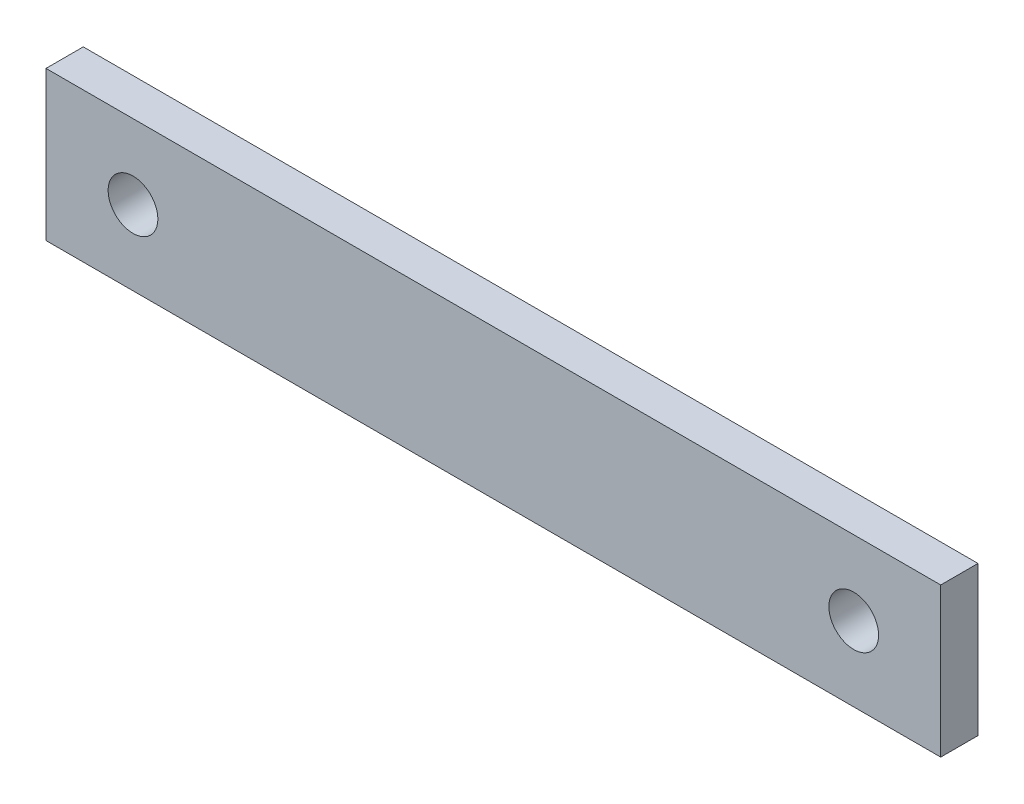
SolidWorks part; units mm, degrees
ref_plane "Plan de face" through (0, 0, 0) normal (0, 0, 1) x (1, 0, 0)
ref_plane "Plan de dessus" through (0, 0, 0) normal (0, 1, 0) x (1, 0, 0)
ref_plane "Plan de droite" through (0, 0, 0) normal (1, 0, 0) x (0, 0, -1)
sketch "Esquisse1" plane through (0, 0, 0) normal (0, 0, 1) x (1, 0, 0)
  line L0 (-24.595, 4.4308) -> (18.605, 4.4308)
  line L1 (-24.595, 4.4308) -> (-24.595, -2.7692)
  line L2 (-24.595, -2.7692) -> (18.605, -2.7692)
  line L3 (18.605, -2.7692) -> (18.605, 4.4308)
  dimension "D1" = 43.2
  dimension "D2" = 7.2
extrude "Boss.-Extru.1" add sketch "Esquisse1" along normal blind 1.8
sketch "Esquisse2" plane through (0, 0, 0) normal (0, 0, 1) x (1, 0, 0)
  line L0 (-24.595, 0.8308) -> (18.605, 0.8308) construction
  line L1 (-24.595, 4.4308) -> (-24.595, -2.7692) construction
  line L2 (18.605, -2.7692) -> (18.605, 4.4308) construction
  line L3 (18.605, 0.8308) -> (14.405, 0.8308) construction
  line L4 (-2.995, 0.8308) -> (-2.995, -6.5149) construction
  line L5 (-2.995, -6.5149) -> (-2.995, 7.0571) construction
  circle A0 centre (14.405, 0.8308) radius 1.2
  circle A1 centre (-20.395, 0.8308) radius 1.2
  dimension "D2" = 2.4
  dimension "D1" = 4.2
extrude "Enlèv. mat.-Extru.1" cut sketch "Esquisse2" along normal blind 1.8
